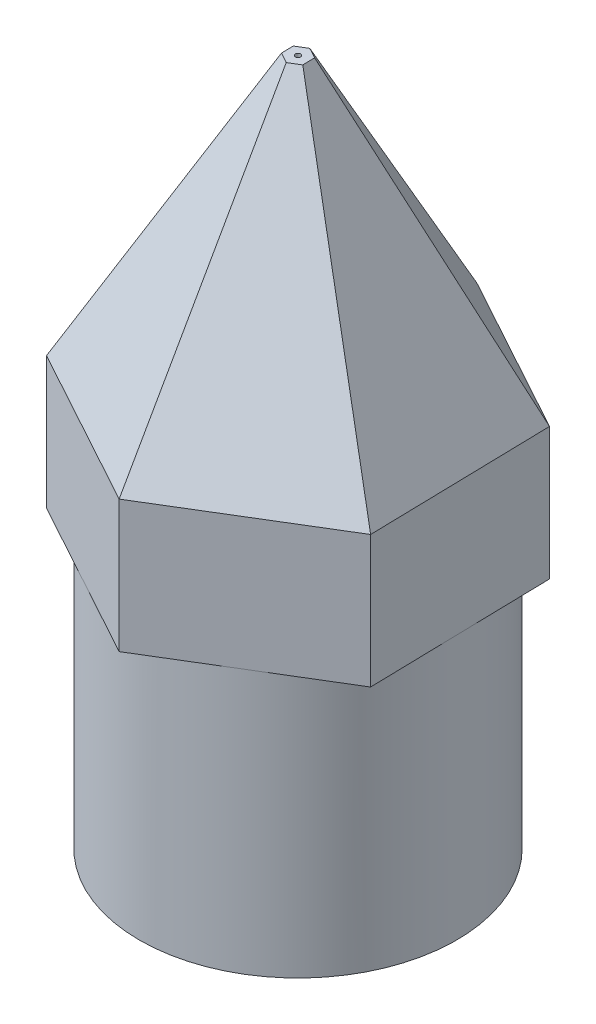
SolidWorks part; units mm, degrees
ref_plane "前视基准面" through (0, 0, 0) normal (0, 0, 1) x (1, 0, 0)
ref_plane "上视基准面" through (0, 0, 0) normal (0, 1, 0) x (1, 0, 0)
ref_plane "右视基准面" through (0, 0, 0) normal (1, 0, 0) x (0, 0, -1)
sketch "草图1" plane through (0, 0, 0) normal (0, 1, 0) x (1, 0, 0)
  circle A0 centre (0, 0) radius 3
  dimension "D1" = 6
extrude "凸台-拉伸1" add sketch "草图1" along normal blind 5
sketch "草图2" plane through (0, 5, 0) normal (0, 1, 0) x (1, 0, 0)
  line L1 (3.0384, -1.6639) -> (2.9601, 1.7994)
  line L2 (2.9601, 1.7994) -> (-0.0782, 3.4632)
  line L3 (-0.0782, 3.4632) -> (-3.0384, 1.6639)
  line L4 (-3.0384, 1.6639) -> (-2.9601, -1.7994)
  line L5 (-2.9601, -1.7994) -> (0.0782, -3.4632)
  line L6 (0.0782, -3.4632) -> (3.0384, -1.6639)
  circle A0 centre (0, 0) radius 3 construction
  dimension "D1" = 6
extrude "凸台-拉伸2" add sketch "草图2" along normal blind 2.5
sketch "草图4" plane through (0, 7.5, 0) normal (0, 1, 0) x (1, 0, 0)
  line L6 (0.0782, -3.4632) -> (3.0384, -1.6639)
  line L7 (3.0384, -1.6639) -> (2.9601, 1.7994)
  line L8 (2.9601, 1.7994) -> (-0.0782, 3.4632)
  line L9 (-0.0782, 3.4632) -> (-3.0384, 1.6639)
  line L10 (-3.0384, 1.6639) -> (-2.9601, -1.7994)
  line L11 (-2.9601, -1.7994) -> (0.0782, -3.4632)
  line L12 (0.0782, -3.4632) -> (3.0384, -1.6639)
  line L13 (3.0384, -1.6639) -> (2.9601, 1.7994)
  line L14 (2.9601, 1.7994) -> (-0.0782, 3.4632)
  line L15 (-0.0782, 3.4632) -> (-3.0384, 1.6639)
  line L16 (-3.0384, 1.6639) -> (-2.9601, -1.7994)
  line L17 (-2.9601, -1.7994) -> (0.0782, -3.4632)
  dimension "D1" = 0
extrude "凸台-拉伸3" add sketch "草图4" along normal blind 5.5 draft 27
sketch "草图5" plane through (0, 13, 0) normal (0, 1, 0) x (1, 0, 0)
  circle A0 centre (0, 0) radius 0.05
  dimension "D1" = 0.1
extrude "切除-拉伸1" cut sketch "草图5" against normal through all
sketch "草图6" plane through (0, 0, 0) normal (0, -1, 0) x (1, 0, 0)
  circle A0 centre (-0.05, 0) radius 2.1275
  circle A1 centre (0, 0) radius 0.05 construction
extrude "切除-拉伸2" cut sketch "草图6" against normal blind 7.5 draft 15
